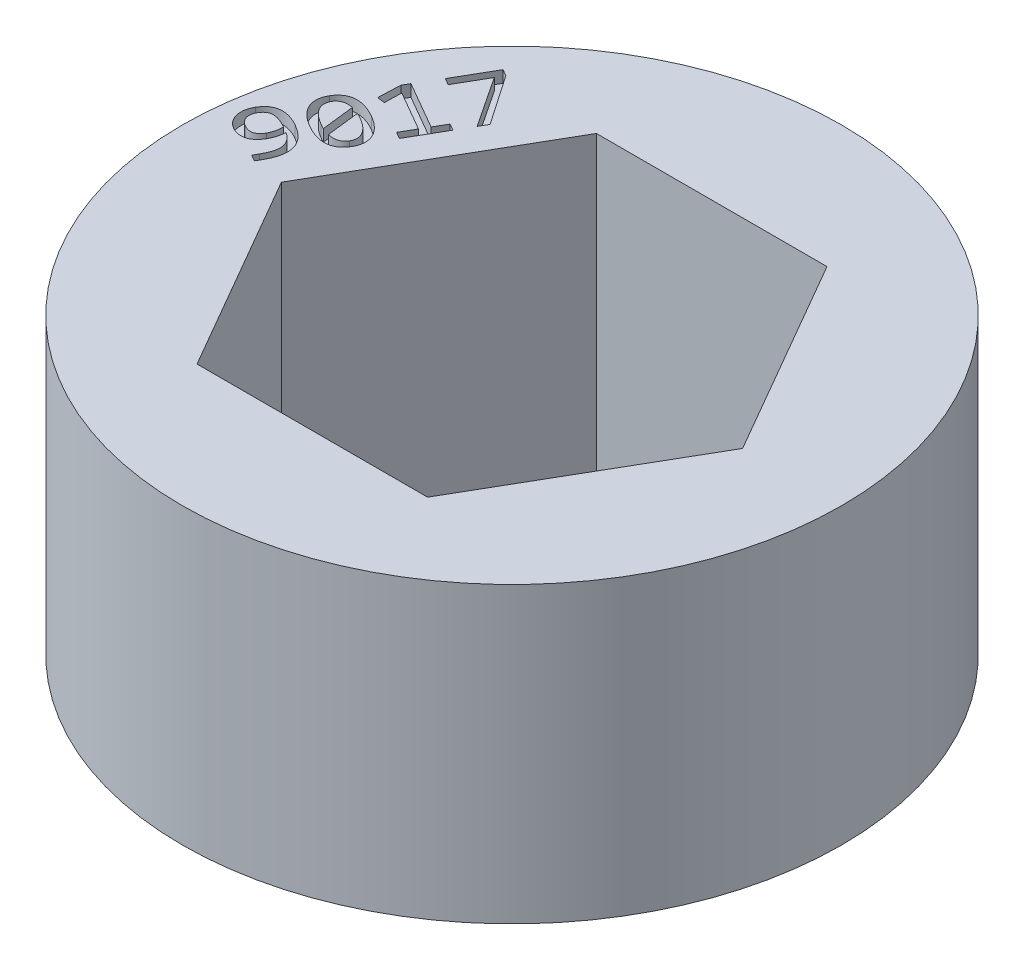
SolidWorks part; units mm, degrees
material "Nylon 101"
ref_plane "Front Plane" through (0, 0, 0) normal (0, 0, 1) x (1, 0, 0)
ref_plane "Top Plane" through (0, 0, 0) normal (0, 1, 0) x (1, 0, 0)
ref_plane "Right Plane" through (0, 0, 0) normal (1, 0, 0) x (0, 0, -1)
sketch "Sketch1" plane through (0, 0, 0) normal (0, 1, 0) x (1, 0, 0)
  line L1 (-3.8861, 6.731) -> (-7.7723, 0)
  line L2 (-7.7723, 0) -> (-3.8861, -6.731)
  line L3 (-3.8861, -6.731) -> (3.8861, -6.731)
  line L4 (3.8861, -6.731) -> (7.7723, 0)
  line L5 (7.7723, 0) -> (3.8861, 6.731)
  line L6 (3.8861, 6.731) -> (-3.8861, 6.731)
  circle A0 centre (0, 0) radius 6.731 construction
  circle A1 centre (0, 0) radius 11.1125
  dimension "D1" = 13.462
  dimension "D2" = 22.225
extrude "Boss-Extrude1" add sketch "Sketch1" along normal blind 9.906
sketch "Sketch2" plane through (0, 9.906, 0) normal (0, 1, 0) x (1, 0, 0)
  line L0 (-9.7148, -1.3326) -> (-4.6895, 7.3715) construction
  line L5 (-3.8861, 6.731) -> (-7.7723, 0) construction
  text T0 "9017\r\n" font "Consolas" height in points 8
  dimension "D1" = 1.016
extrude "Cut-Extrude1" cut sketch "Sketch2" against normal blind 0.4
